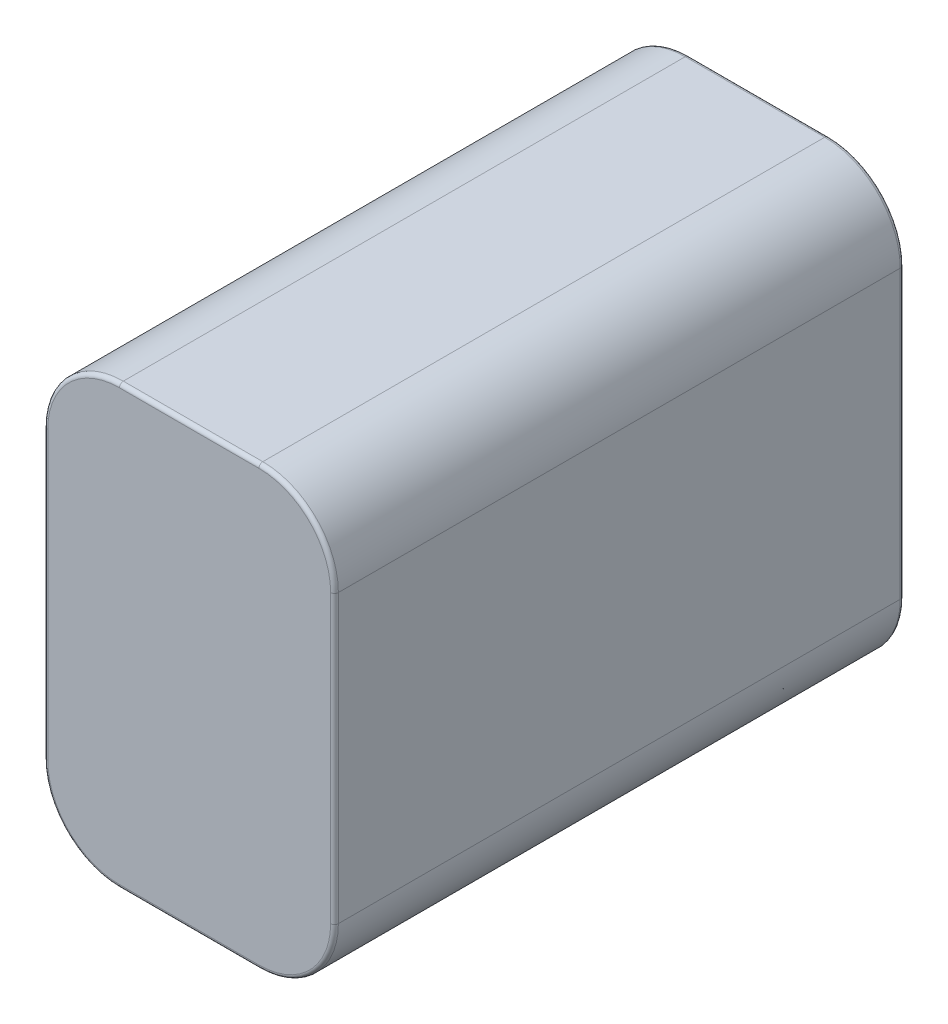
SolidWorks part; units mm, degrees
material "ABS"
ref_plane "Front Plane" through (0, 0, 0) normal (0, 0, 1) x (1, 0, 0)
ref_plane "Top Plane" through (0, 0, 0) normal (0, 1, 0) x (1, 0, 0)
ref_plane "Right Plane" through (0, 0, 0) normal (1, 0, 0) x (0, 0, -1)
sketch "Sketch1" plane through (0, 0, 0) normal (0, 0, 1) x (1, 0, 0)
  line L1 (0, -28.25) -> (18, -28.25)
  line L2 (-9.75, -18.5) -> (-9.75, 18.5)
  line L3 (0, 28.25) -> (18, 28.25)
  line L4 (27.75, -18.5) -> (27.75, 18.5)
  line L5 (-9.75, -28.25) -> (27.75, 28.25) construction
  line L6 (-9.75, 28.25) -> (27.75, -28.25) construction
  circle A0 centre (18, 0) radius 9 construction
  arc A1 (-9.75, 18.5) -> (0, 28.25) centre (0, 18.5) cw
  arc A2 (0, -28.25) -> (-9.75, -18.5) centre (0, -18.5) cw
  arc A3 (18, -28.25) -> (27.75, -18.5) centre (18, -18.5) ccw
  arc A4 (18, 28.25) -> (27.75, 18.5) centre (18, 18.5) cw
  circle A5 centre (0, 0) radius 9 construction
  point P0 (9, 0)
  dimension "D1" = 56.5
  dimension "D3" = 9.75
  dimension "D2" = 37.5
extrude "Boss-Extrude1" add sketch "Sketch1" along normal blind 0.75
sketch "Sketch2" plane through (0, 0, 0) normal (0, 0, -1) x (-1, 0, 0)
  line L0 (-27, 18) -> (-27, -18)
  line L1 (-18, -27) -> (0, -27)
  line L2 (9, 18) -> (9, -18)
  line L3 (0, 27) -> (-18, 27)
  line L4 (0, 28.25) -> (-18, 28.25)
  line L5 (-27.75, 18.5) -> (-27.75, -18.5)
  line L6 (-18, -28.25) -> (0, -28.25)
  line L7 (9.75, -18.5) -> (9.75, 18.5)
  line L8 (0, 28.25) -> (-18, 28.25)
  line L9 (-27.75, 18.5) -> (-27.75, -18.5)
  line L10 (-18, -28.25) -> (0, -28.25)
  line L11 (9.75, -18.5) -> (9.75, 18.5)
  circle A0 centre (-18, -18) radius 9 construction
  circle A1 centre (0, -18) radius 9 construction
  circle A2 centre (-18, 18) radius 9 construction
  circle A3 centre (0, 18) radius 9 construction
  arc A4 (9.75, 18.5) -> (0, 28.25) centre (0, 18.5) ccw
  arc A5 (-18, 28.25) -> (-27.75, 18.5) centre (-18, 18.5) ccw
  arc A6 (-27.75, -18.5) -> (-18, -28.25) centre (-18, -18.5) ccw
  arc A7 (0, -28.25) -> (9.75, -18.5) centre (0, -18.5) ccw
  arc A8 (9.75, 18.5) -> (0, 28.25) centre (0, 18.5) ccw
  arc A9 (-18, 28.25) -> (-27.75, 18.5) centre (-18, 18.5) ccw
  arc A10 (-27.75, -18.5) -> (-18, -28.25) centre (-18, -18.5) ccw
  arc A11 (0, -28.25) -> (9.75, -18.5) centre (0, -18.5) ccw
  arc A12 (-27, -18) -> (-18, -27) centre (-18, -18) ccw
  arc A13 (0, -27) -> (9, -18) centre (0, -18) ccw
  arc A14 (-18, 27) -> (-27, 18) centre (-18, 18) ccw
  arc A15 (9, 18) -> (0, 27) centre (0, 18) ccw
  dimension "D1" = 0
extrude "Boss-Extrude2" add sketch "Sketch2" along normal up to surface (65 mm away)
sketch "Sketch3" plane through (0, 0, -65) normal (0, 0, -1) x (-1, 0, 0)
  line L4 (9.75, -18.5) -> (9.75, 18.5)
  line L5 (0, 28.25) -> (-18, 28.25)
  line L6 (-27.75, 18.5) -> (-27.75, -18.5)
  line L7 (-18, -28.25) -> (0, -28.25)
  line L8 (9.75, -18.5) -> (9.75, 18.5)
  line L9 (0, 28.25) -> (-18, 28.25)
  line L10 (-27.75, 18.5) -> (-27.75, -18.5)
  line L11 (-18, -28.25) -> (0, -28.25)
  arc A4 (9.75, 18.5) -> (0, 28.25) centre (0, 18.5) ccw
  arc A5 (-18, 28.25) -> (-27.75, 18.5) centre (-18, 18.5) ccw
  arc A6 (-27.75, -18.5) -> (-18, -28.25) centre (-18, -18.5) ccw
  arc A7 (0, -28.25) -> (9.75, -18.5) centre (0, -18.5) ccw
  arc A8 (9.75, 18.5) -> (0, 28.25) centre (0, 18.5) ccw
  arc A9 (-18, 28.25) -> (-27.75, 18.5) centre (-18, 18.5) ccw
  arc A10 (-27.75, -18.5) -> (-18, -28.25) centre (-18, -18.5) ccw
  arc A11 (0, -28.25) -> (9.75, -18.5) centre (0, -18.5) ccw
  dimension "D1" = 0
extrude "Boss-Extrude3" add sketch "Sketch3" along normal offset from surface (7.75 mm away) 73.5 up to face at (9, 0, 0.75)
fillet "Fillet1" radius 0.5 16 edges at (9, 28.25, 0.75) (24.8943, 25.3943, 0.75) (27.75, 0, 0.75) (24.8943, -25.3943, 0.75) (9, -28.25, 0.75) (-6.8943, -25.3943, 0.75) (-9.75, 0, 0.75) (-6.8943, 25.3943, 0.75) (24.8943, -25.3943, -72.75) (27.75, 0, -72.75) (24.8943, 25.3943, -72.75) (9, 28.25, -72.75) (-6.8943, 25.3943, -72.75) (-9.75, 0, -72.75) (-6.8943, -25.3943, -72.75) (9, -28.25, -72.75)
